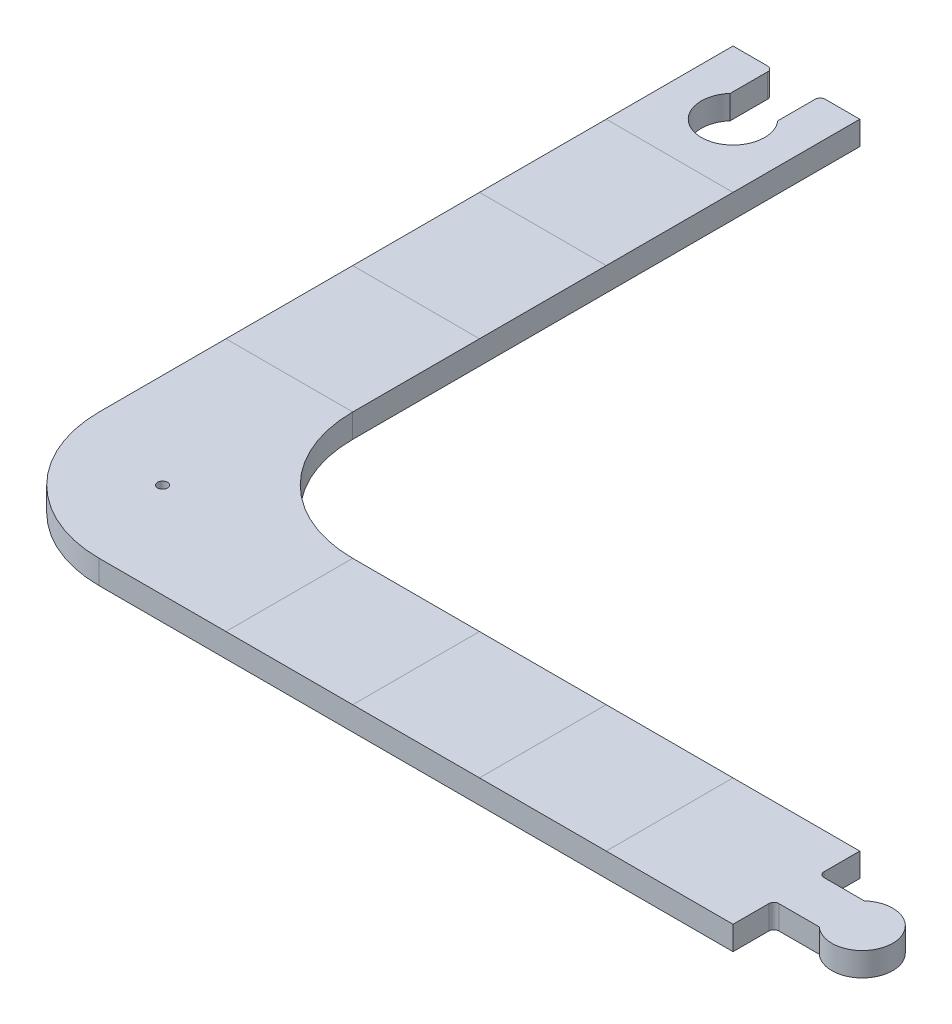
SolidWorks part; units mm, degrees
ref_plane "Front Plane" through (0, 0, 0) normal (0, 0, 1) x (1, 0, 0)
ref_plane "Top Plane" through (0, 0, 0) normal (0, 1, 0) x (1, 0, 0)
ref_plane "Right Plane" through (0, 0, 0) normal (1, 0, 0) x (0, 0, -1)
sketch "Sketch1" plane through (0, 0, 0) normal (0, 1, 0) x (1, 0, 0)
  line L0 (12.7, 146.05) -> (12.7, 12.7) construction
  line L1 (25.4, 0) -> (152.4, 0)
  line L2 (0, 25.4) -> (0, 152.4)
  line L3 (0, 152.4) -> (6.9375, 152.4)
  line L7 (152.4, 25.4) -> (50.8, 25.4)
  line L8 (25.4, 152.4) -> (25.4, 50.8)
  line L9 (162.0395, 12.7) -> (155.6895, 12.7) construction
  line L10 (17.4625, 151.4) -> (17.4625, 143.9001)
  line L11 (7.9375, 151.4) -> (7.9375, 143.9001)
  line L12 (18.4625, 152.4) -> (25.4, 152.4)
  line L16 (155.6895, 12.7) -> (12.7, 12.7) construction
  line L17 (153.4, 8.1875) -> (161.4954, 8.1875)
  line L18 (153.4, 17.2125) -> (161.4954, 17.2125)
  line L19 (152.4, 25.4) -> (152.4, 18.2125)
  line L20 (152.4, 7.1875) -> (152.4, 0)
  arc A0 (0, 25.4) -> (25.4, 0) centre (25.4, 25.4) ccw
  arc A1 (25.4, 50.8) -> (50.8, 25.4) centre (50.8, 50.8) ccw
  arc A2 (7.9375, 143.9001) -> (17.4625, 143.9001) centre (12.7, 139.7) ccw
  arc A4 (161.4954, 8.1875) -> (161.4954, 17.2125) centre (165.6, 12.7) ccw
  arc A5 (152.4, 7.1875) -> (153.4, 8.1875) centre (153.4, 7.1875) cw
  arc A6 (152.4, 18.2125) -> (153.4, 17.2125) centre (153.4, 18.2125) ccw
  arc A7 (18.4625, 152.4) -> (17.4625, 151.4) centre (18.4625, 151.4) ccw
  arc A8 (6.9375, 152.4) -> (7.9375, 151.4) centre (6.9375, 151.4) cw
  point P9 (0, 0)
  point P28 (0, 0)
  point P33 (17.4625, 152.4)
  dimension "D3" = 25.4
  dimension "D6" = 12.7
  dimension "D7" = 12.7
  dimension "D4" = 13.2
  dimension "D12" = 1
  dimension "D13" = 6.1
  dimension "D1" = 25.4
  dimension "D2" = 25.4
  dimension "D5" = 152.4
  dimension "D8" = 9.525
  dimension "D9" = 4.7625
  dimension "D10" = 9.025
  dimension "D11" = 4.5125
  dimension "D14" = 152.4
extrude "Boss-Extrude1" add sketch "Sketch1" along normal blind 4.7625
sketch "Sketch2" plane through (0, 4.7625, 0) normal (0, 1, 0) x (1, 0, 0)
  line L0 (0, 0) -> (59.005, 59.005) construction
  line L1 (0, 0) -> (77.7961, 0) construction
  line L2 (25.4, 0) -> (152.4, 0) construction
  circle A0 centre (19.05, 19.05) radius 1
  point P5 (0, 0)
  dimension "D2" = 2
  dimension "D1" = 45
  dimension "D3" = 19.05
extrude "Cut-Extrude1" cut sketch "Sketch2" against normal blind 8.89
sketch "Sketch3" plane through (0, 4.7625, 0) normal (0, 1, 0) x (1, 0, 0)
  line L0 (127, 25.4) -> (127, 0)
  line L1 (152.4, 25.4) -> (50.8, 25.4) construction
  line L2 (25.4, 0) -> (152.4, 0) construction
  line L3 (152.4, 18.2125) -> (152.4, 25.4) construction
  line L4 (101.6, 25.4) -> (101.6, 0)
  line L5 (76.2, 25.4) -> (76.2, 0)
  line L6 (50.8, 25.4) -> (50.8, 0)
  line L7 (0, 127) -> (25.4, 127)
  line L8 (0, 152.4) -> (0, 25.4) construction
  line L9 (25.4, 50.8) -> (25.4, 152.4) construction
  line L10 (6.9375, 152.4) -> (0, 152.4) construction
  line L11 (0, 101.6) -> (25.4, 101.6)
  line L12 (0, 76.2) -> (25.4, 76.2)
  line L13 (0, 50.8) -> (25.4, 50.8)
  dimension "D1" = 25.4
  dimension "D3" = 25.4
  dimension "D2" = 4
  dimension "D4" = 4
split line "Split Line1"
